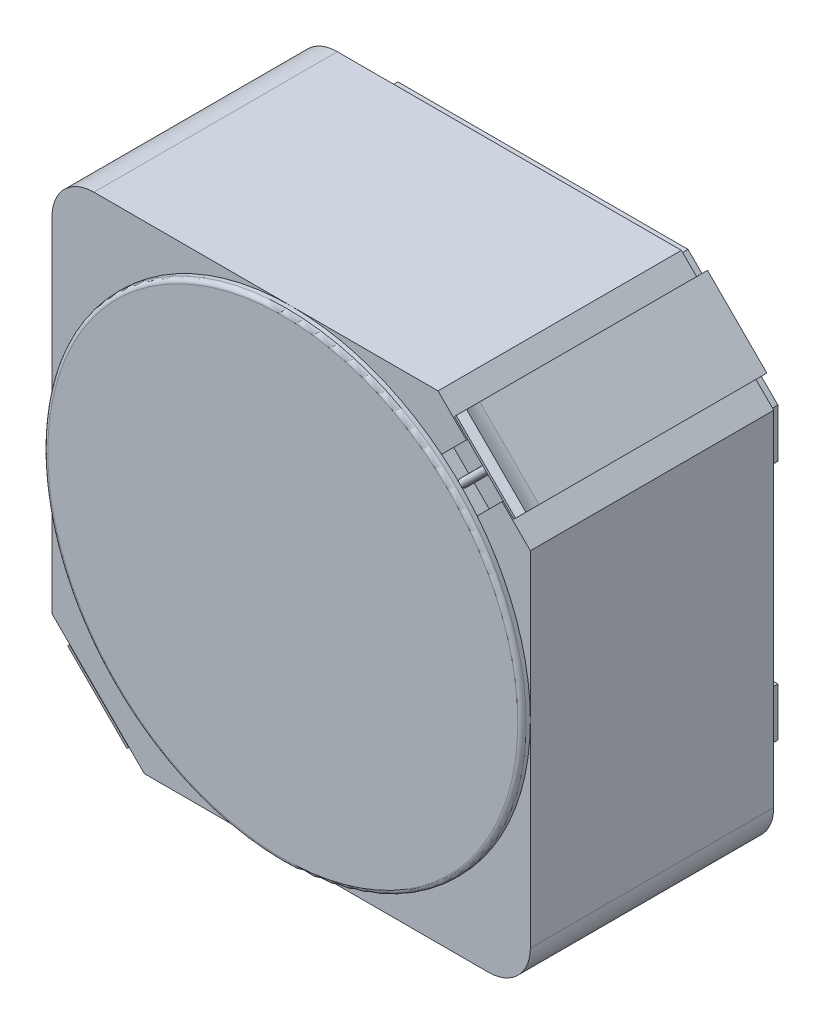
SolidWorks part; units mm, degrees
ref_plane "Спереди" through (0, 0, 0) normal (0, 0, 1) x (1, 0, 0)
ref_plane "Сверху" through (0, 0, 0) normal (0, 1, 0) x (1, 0, 0)
ref_plane "Справа" through (0, 0, 0) normal (1, 0, 0) x (0, 0, -1)
sketch "Эскиз1" plane through (0, 0, 0) normal (0, 0, 1) x (1, 0, 0)
  line L0 (-2.85, -1.75) -> (-1.75, -2.85)
  line L1 (-2.35, 2.85) -> (1.75, 2.85)
  line L2 (-2.85, 2.35) -> (-2.85, -1.75)
  line L3 (-1.75, -2.85) -> (2.35, -2.85)
  line L4 (2.85, 1.75) -> (2.85, -2.35)
  line L5 (-2.85, 2.85) -> (2.85, -2.85) construction
  line L6 (-2.85, -2.85) -> (2.85, 2.85) construction
  line L7 (1.75, 2.85) -> (2.85, 1.75)
  arc A0 (-2.35, 2.85) -> (-2.85, 2.35) centre (-2.35, 2.35) ccw
  arc A1 (2.35, -2.85) -> (2.85, -2.35) centre (2.35, -2.35) ccw
  point P0 (0, 0)
  dimension "D1" = 0.5
  dimension "D2" = 5.7
extrude "Корпус" add sketch "Эскиз1" along normal blind 2.9 from offset 0.1
sketch "Эскиз2" plane through (0, 0, 3) normal (0, 0, 1) x (1, 0, 0)
  line L0 (-2.85, 2.35) -> (-2.85, -1.75) construction
  circle A0 centre (0, 0) radius 2.85
extrude "Сердечник" add sketch "Эскиз2" along normal blind 0.1 and the other way blind 1
fillet "Скругление1" radius 0.05 1 edges at (2.85, 0, 3.1)
ref_plane "Плоскость1" through (0.55, -0.55, 0) normal (0.7071, -0.7071, 0) x (0, 0, 1)
sketch "Эскиз6" plane through (0.55, -0.55, 0) normal (0.7071, -0.7071, 0) x (0, 0, 1)
  line L0 (2.908, -3.3477) -> (2.995, -3.2957)
  line L1 (2.995, -3.2657) -> (0.125, -3.2657)
  line L2 (2.715, -3.2957) -> (0, -3.2957)
  line L3 (0, -3.2957) -> (0, -2.7657)
  line L4 (0.125, -3.2657) -> (0.125, -2.7657)
  line L5 (0.125, -2.7657) -> (0, -2.7657)
  line L6 (2.995, -3.2957) -> (2.995, -3.2657)
  line L8 (0.1, -3.2527) -> (3, -3.2527) construction
  line L9 (3, -2.85) -> (3, -2.0153) construction
  line L11 (0.1, 0.3536) -> (0.1, 3.2527) construction
  line L12 (3, -3.2527) -> (0.1, -3.2527) construction
  spline S0 degree 2 poles (2.715, -3.2957) (2.8188, -3.2995) (2.908, -3.3477) knots 0 0 0 1 1 1
  dimension "D2" = 0.5
  dimension "D3" = 0.013
  dimension "D4" = 0.025
  dimension "D5" = 0.005
  dimension "D6" = 0.082
  dimension "D7" = 0.087
  dimension "D8" = 120.867
  dimension "D9" = 0.28
  dimension "D10" = 0.1354
  dimension "D11" = 0.0295
  dimension "D12" = 0.03
extrude "вывод, бок" add sketch "Эскиз6" against normal blind 1 from offset 0.3 offset against normal yes
ref_point "Точка1"
ref_axis "Ось1" through (0, 0, 3.1) along (0, 0, -1)
sketch "Эскиз8" plane through (0, 0, 3) normal (0, 0, 1) x (1, 0, 0)
  line L0 (2.5121, 2.0879) -> (2.0879, 2.5121)
  line L2 (2.0879, 2.5121) -> (1.7357, 2.16)
  line L3 (-1.6879, -2.1121) -> (-1.3425, -1.7534)
  line L4 (1.9479, 1.9479) -> (0, 0) construction
  line L5 (2.5121, 2.0879) -> (2.16, 1.7357)
  line L6 (2.16, 1.7357) -> (1.7357, 2.16)
  line L7 (-1.7748, -1.3372) -> (-1.3425, -1.7534)
  line L8 (-2.1201, -1.696) -> (-1.7748, -1.3372)
  line L9 (-2.1201, -1.696) -> (-1.6879, -2.1121)
  line L10 (2.85, 1.75) -> (1.75, 2.85) construction
  dimension "D2" = 0.498
  dimension "D4" = 0.6
  dimension "D1" = 2
extrude "Вытянуть8" cut sketch "Эскиз8" against normal blind 0.2
sketch "Эскиз9" plane through (2.3092, 2.3092, 0) normal (-0.7071, -0.7071, 0) x (0, 0, 1)
  line L1 (0, 0) -> (2.899, 0) construction
  line L2 (2.995, 0.5222) -> (2.995, -0.4778) construction
  circle A0 centre (2.899, 0) radius 0.046
  dimension "D1" = 0.092
  dimension "D2" = 0.096
extrude "Бобышка-Вытянуть1" add sketch "Эскиз9" along normal up to next (0.511 mm away) and the other way blind 0.05 draft 45 from offset 0.05
pattern_circular "Круговой массив3" count 2 over 360 about axis through (0, 0, 3.1) along (0, 0, -1) of "вывод, бок", "Бобышка-Вытянуть1"
sketch "Эскиз13" plane through (0, 0, 0.1) normal (0, 0, -1) x (-1, 0, 0)
  line L1 (-2.85, -2.35) -> (-2.85, 1.75) construction
  line L2 (0, -2.8) -> (0, 0) construction
  line L3 (2.85, 2.35) -> (2.85, -1.75) construction
  line L4 (1.9308, -2.6692) -> (1.75, -2.85) construction
  line L5 (55, 0) -> (-55, 0) construction
  line L6 (2.05, 1.1488) -> (2.8, 1.1488)
  line L7 (1.75, -2.85) -> (-2.35, -2.85) construction
  line L8 (2.8, 1.1488) -> (2.8, 1.7288)
  line L9 (1.7288, 2.8) -> (2.8, 1.7288)
  line L10 (-1.7288, 2.8) -> (1.7288, 2.8)
  line L11 (-2.8, 1.7288) -> (-1.7288, 2.8)
  line L12 (-2.8, -1.1488) -> (-2.05, -1.1488)
  line L13 (-2.8, -1.7288) -> (-2.8, -1.1488)
  line L16 (-2.8, -1.7288) -> (-1.7288, -2.8)
  line L17 (-2.8, 1.7288) -> (-2.8, 1.1488)
  line L18 (-1.7288, -2.8) -> (1.7288, -2.8)
  line L19 (1.7288, -2.8) -> (2.8, -1.7288)
  line L20 (2.8, -1.1488) -> (2.8, -1.7288)
  line L21 (2.05, -1.1488) -> (2.8, -1.1488)
  line L22 (-2.8, 1.1488) -> (-2.05, 1.1488)
  arc A0 (-2.05, -1.1488) -> (2.05, -1.1488) centre (0, 0) ccw
  arc A1 (-2.05, 1.1488) -> (2.05, 1.1488) centre (0, 0) cw
  circle A2 centre (0, 0) radius 2.85 construction
  dimension "D2" = 0.5
  dimension "D3" = 0.75
  dimension "D5" = 0.05
  dimension "D6" = 0.0503
  dimension "D7" = 0.05
  dimension "D1" = 0.58
extrude "Выводы низ" add sketch "Эскиз13" along normal up to surface (0.1 mm away) up to face at (-2.1273, -2.1587, 0)
